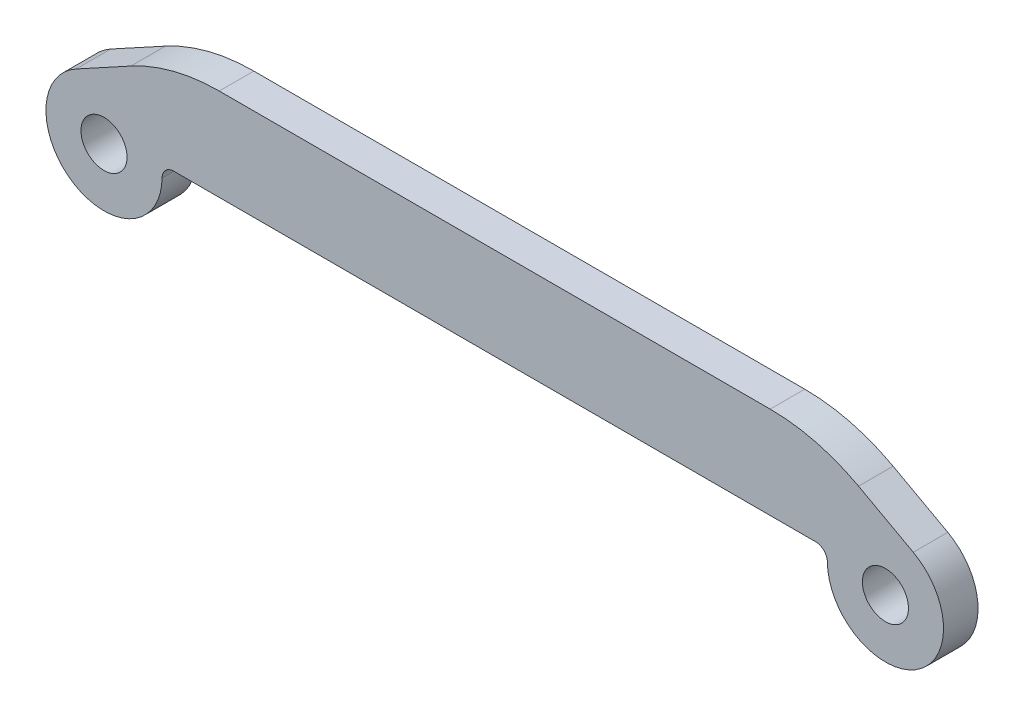
SolidWorks part; units mm, degrees
ref_plane "Front Plane" through (0, 0, 0) normal (0, 0, 1) x (1, 0, 0)
ref_plane "Top Plane" through (0, 0, 0) normal (0, 1, 0) x (1, 0, 0)
ref_plane "Right Plane" through (0, 0, 0) normal (1, 0, 0) x (0, 0, -1)
sketch "Sketch1" plane through (0, 0, 0) normal (0, 0, 1) x (1, 0, 0)
  line L0 (0, -1466.0297) -> (0, 71835.4576) construction
  line L1 (-22.225, 0) -> (22.225, 0)
  line L2 (-22.225, 0) -> (-28.8416, -3.6137)
  line L3 (-22.9235, -7.1247) -> (-22.9235, -6.35)
  line L4 (-25.5384, -6.35) -> (22.9235, -6.35)
  line L5 (22.9235, -7.1247) -> (22.9235, -6.35)
  line L6 (22.225, 0) -> (28.8416, -3.6137)
  arc A0 (-28.8416, -3.6137) -> (-22.9235, -7.1247) centre (-26.924, -7.1247) ccw
  circle A1 centre (-26.924, -7.1247) radius 1.5875
  circle A2 centre (26.924, -7.1247) radius 1.5875
  arc A3 (28.8416, -3.6137) -> (22.9235, -7.1247) centre (26.924, -7.1247) cw
  point P11 (-26.924, -11.1252)
  dimension "D2" = 3.175
  dimension "D3" = 4.0005
  dimension "D1" = 44.45
  dimension "D4" = 4.7752
  dimension "D5" = 6.35
  dimension "D6" = 53.848
extrude "Boss-Extrude1" add sketch "Sketch1" along normal mid plane 2.3813
fillet "Fillet1" radius 12.7 2 edges at (22.225, 0, 0) (-22.225, 0, 0)
fillet "Fillet2" radius 0.8128 2 edges at (22.9235, -6.35, 0) (-22.9235, -6.35, 0)
